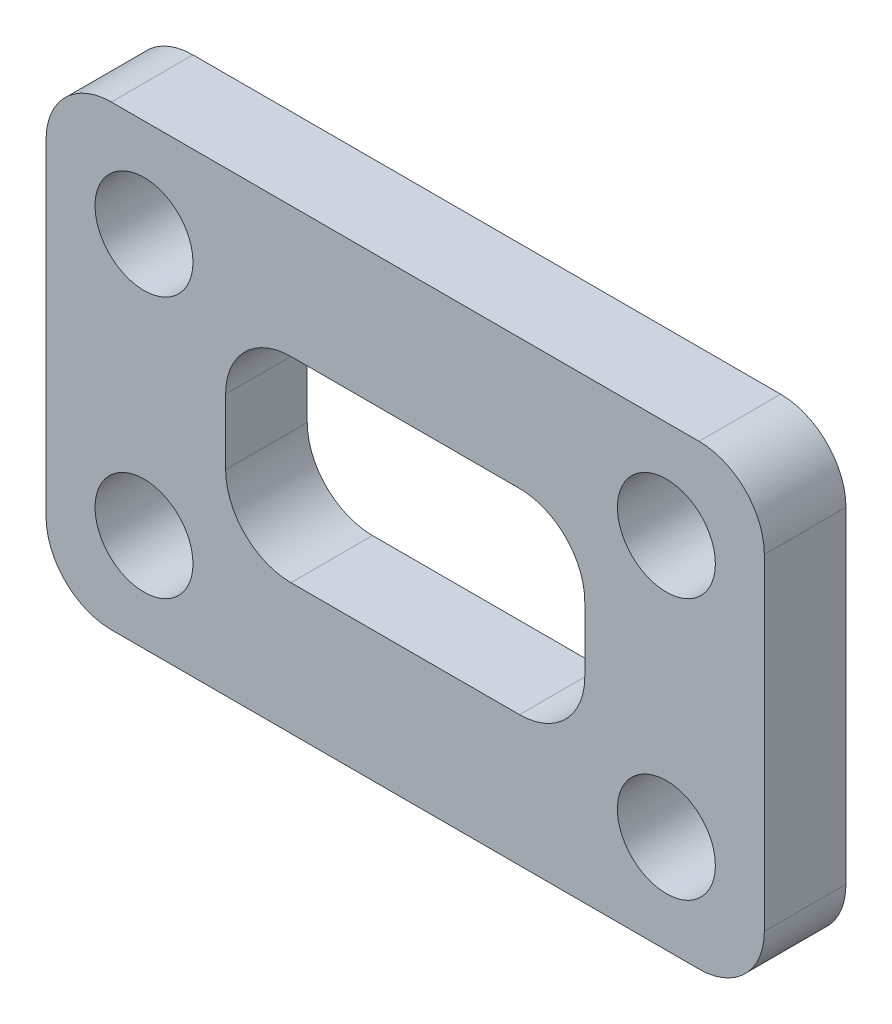
SolidWorks part; units mm, degrees
material "Thornel Mat VMA"
ref_plane "前视基准面" through (0, 0, 0) normal (0, 0, 1) x (1, 0, 0)
ref_plane "上视基准面" through (0, 0, 0) normal (0, 1, 0) x (1, 0, 0)
ref_plane "右视基准面" through (0, 0, 0) normal (1, 0, 0) x (0, 0, -1)
other "Configuration Table"
sketch "草图1" plane through (0, 0, 0) normal (0, 0, 1) x (1, 0, 0)
  line L1 (-11, -7) -> (11, -7)
  line L2 (-11, -7) -> (-11, 7)
  line L3 (-11, 7) -> (11, 7)
  line L4 (11, -7) -> (11, 7)
  line L5 (-11, -7) -> (11, 7) construction
  line L6 (-11, 7) -> (11, -7) construction
  line L7 (-8, -4) -> (8, -4) construction
  line L8 (-8, -4) -> (-8, 4) construction
  line L9 (-8, 4) -> (8, 4) construction
  line L10 (8, -4) -> (8, 4) construction
  line L11 (-8, -4) -> (8, 4) construction
  line L12 (-8, 4) -> (8, -4) construction
  line L13 (-5.5, -3) -> (5.5, -3)
  line L14 (-5.5, -3) -> (-5.5, 3)
  line L15 (-5.5, 3) -> (5.5, 3)
  line L16 (5.5, -3) -> (5.5, 3)
  line L17 (-5.5, -3) -> (5.5, 3) construction
  line L18 (-5.5, 3) -> (5.5, -3) construction
  circle A0 centre (8, 4) radius 1.5
  circle A1 centre (8, -4) radius 1.5
  circle A2 centre (-8, -4) radius 1.5
  circle A3 centre (-8, 4) radius 1.5
  point P0 (0, 0)
  point P6 (0, 0)
  point P15 (0, 0)
  dimension "D2" = 3
  dimension "D1" = 8
  dimension "D3" = 3
  dimension "D4" = 1
  dimension "D5" = 16
  dimension "D6" = 3
  dimension "D7" = 2.5
extrude "凸台-拉伸1" add sketch "草图1" along normal blind 2.5
fillet "圆角1" radius 2 8 edges at (5.5, 3, 1.25) (-5.5, -3, 1.25) (5.5, -3, 1.25) (11, -7, 1.25) (-11, -7, 1.25) (-11, 7, 1.25) (11, 7, 1.25) (-5.5, 3, 1.25)
